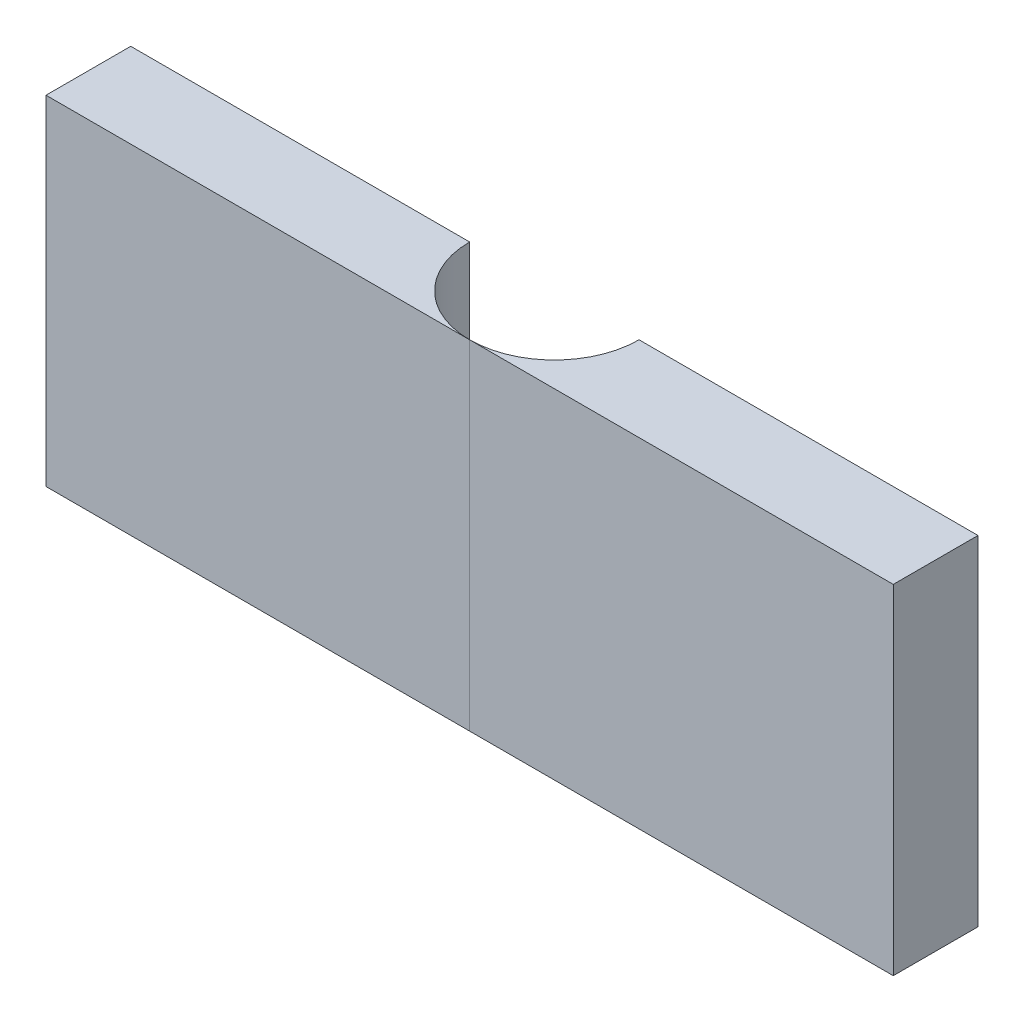
SolidWorks part; units mm, degrees
ref_plane "Front Plane" through (0, 0, 0) normal (0, 0, 1) x (1, 0, 0)
ref_plane "Top Plane" through (0, 0, 0) normal (0, 1, 0) x (1, 0, 0)
ref_plane "Right Plane" through (0, 0, 0) normal (1, 0, 0) x (0, 0, -1)
sketch "Sketch3" plane through (0, 0, 0) normal (0, 1, 0) x (1, 0, 0)
  line L1 (-25, 2.5) -> (25, 2.5)
  line L2 (-25, 2.5) -> (-25, -2.5)
  line L3 (-25, -2.5) -> (25, -2.5)
  line L4 (25, 2.5) -> (25, -2.5)
  line L5 (-25, 2.5) -> (25, -2.5) construction
  line L6 (-25, -2.5) -> (25, 2.5) construction
  point P0 (0, 0)
  dimension "D1" = 50
  dimension "D2" = 5
extrude "Boss-Extrude2" add sketch "Sketch3" against normal blind 20
sketch "Sketch5" plane through (0, 0, 0) normal (0, 1, 0) x (1, 0, 0)
  line L0 (25, 2.5) -> (-25, 2.5) construction
  line L1 (-5, 2.5) -> (5, 2.5)
  arc A0 (5, 2.5) -> (-5, 2.5) centre (0, 2.5) cw
  dimension "D1" = 5
extrude "Cut-Extrude2" cut sketch "Sketch5" against normal blind 20
